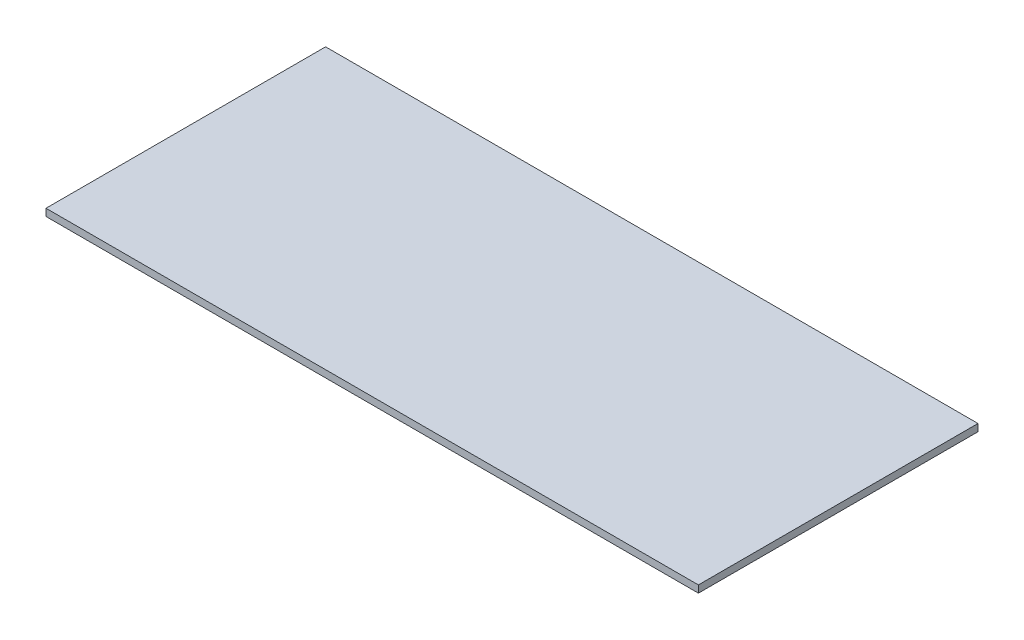
SolidWorks part; units mm, degrees
ref_plane "Front Plane" through (0, 0, 0) normal (0, 0, 1) x (1, 0, 0)
ref_plane "Top Plane" through (0, 0, 0) normal (0, 1, 0) x (1, 0, 0)
ref_plane "Right Plane" through (0, 0, 0) normal (1, 0, 0) x (0, 0, -1)
sketch "Sketch1" plane through (0, 0, 0) normal (0, 1, 0) x (1, 0, 0)
  line L1 (0, 0) -> (182, 0)
  line L2 (0, 0) -> (0, 78)
  line L3 (0, 78) -> (182, 78)
  line L4 (182, 0) -> (182, 78)
  dimension "D1" = 78
  dimension "D2" = 182
extrude "Boss-Extrude1" add sketch "Sketch1" along normal blind 2
